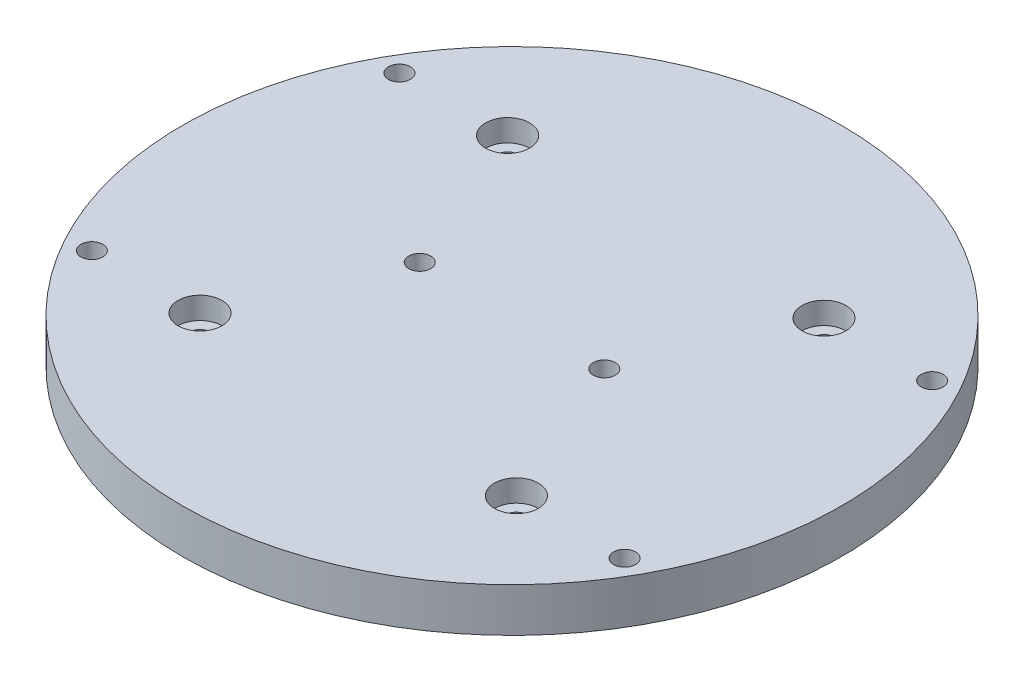
SolidWorks part; units mm, degrees
ref_plane "前视基准面" through (0, 0, 0) normal (0, 0, 1) x (1, 0, 0)
ref_plane "上视基准面" through (0, 0, 0) normal (0, 1, 0) x (1, 0, 0)
ref_plane "右视基准面" through (0, 0, 0) normal (1, 0, 0) x (0, 0, -1)
other "Configuration Table"
sketch "草图1" plane through (0, 0, 0) normal (0, 1, 0) x (1, 0, 0)
  circle A0 centre (0, 0) radius 75
  dimension "D1" = 150
extrude "凸台-拉伸1" add sketch "草图1" along normal blind 10
sketch "草图2" plane through (0, 10, 0) normal (0, 1, 0) x (1, 0, 0)
  line L0 (-104.1191, 0) -> (98.2134, 0) construction
  line L1 (0, 78.3782) -> (0, -83.3851) construction
  line L2 (36, 34.471) -> (36, -33.8291) construction
  line L3 (-36, 18.6798) -> (-36, -19.4501) construction
  line L4 (0, 0) -> (60.6218, 35) construction
  circle A0 centre (21, 0) radius 2.5
  circle A1 centre (-21, 0) radius 2.5
  circle A2 centre (36, 35) radius 2.5
  circle A3 centre (36, -35) radius 2.5
  circle A4 centre (-36, -35) radius 2.5
  circle A5 centre (-36, 35) radius 2.5
  circle A6 centre (60.6218, 35) radius 2.5
  circle A7 centre (60.6218, -35) radius 2.5
  circle A8 centre (-60.6218, -35) radius 2.5
  circle A9 centre (-60.6218, 35) radius 2.5
  dimension "D3" = 5
  dimension "D4" = 5
  dimension "D8" = 5
  dimension "D1" = 72
  dimension "D2" = 42
  dimension "D5" = 70
  dimension "D6" = 70
  dimension "D7" = 30
extrude "切除-拉伸1" cut sketch "草图2" against normal blind 27
sketch "草图3" plane through (0, 10, 0) normal (0, 1, 0) x (1, 0, 0)
  circle A0 centre (36, 35) radius 5
  circle A1 centre (36, -35) radius 5
  circle A2 centre (-36, -35) radius 5
  circle A3 centre (-36, 35) radius 5
  dimension "D1" = 10
extrude "切除-拉伸2" cut sketch "草图3" against normal blind 5
